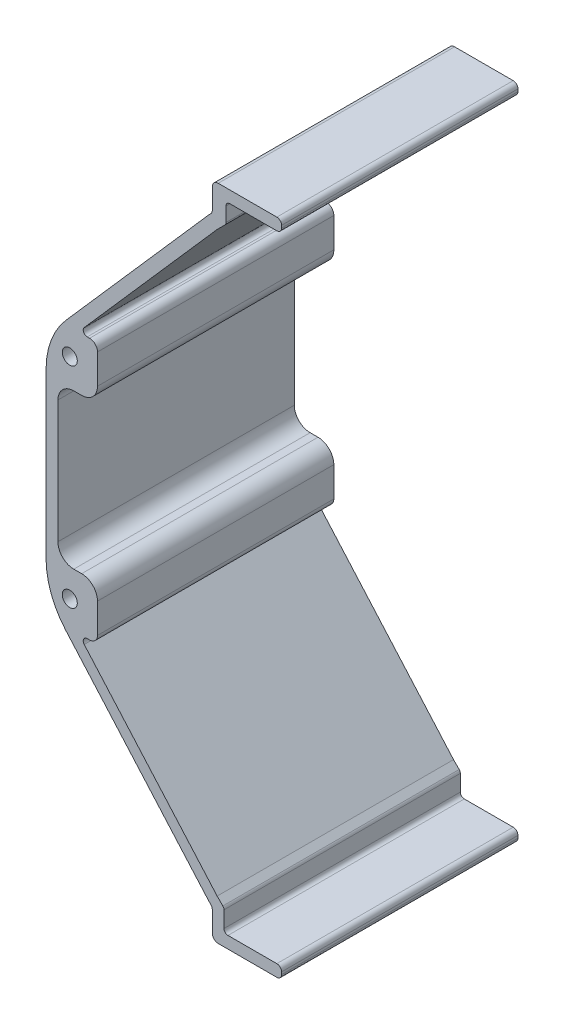
SolidWorks part; units mm, degrees
ref_plane "前视基准面" through (0, 0, 0) normal (0, 0, 1) x (1, 0, 0)
ref_plane "上视基准面" through (0, 0, 0) normal (0, 1, 0) x (1, 0, 0)
ref_plane "右视基准面" through (0, 0, 0) normal (1, 0, 0) x (0, 0, -1)
other "Configuration Table"
sketch "草图1" plane through (0, 0, 0) normal (0, 0, 1) x (1, 0, 0)
  line L0 (-111.7, 80.15) -> (-123.55, 80.15)
  line L1 (-124.55, 79.15) -> (-124.55, 75.5502)
  line L2 (-124.8429, 74.8431) -> (-126.773, 72.913)
  line L3 (-126.773, 72.913) -> (-160.353, 34.6597)
  line L4 (-159.6015, 33) -> (-159, 33)
  line L5 (-157, 31) -> (-157, 23.5)
  line L6 (-161, 19.5) -> (-162.989, 19.5)
  line L7 (-166.989, 15.5) -> (-166.989, -15.5)
  line L8 (-162.989, -19.5) -> (-161, -19.5)
  line L9 (-157, -23.5) -> (-157, -31)
  line L10 (-159, -33) -> (-159.6015, -33)
  line L11 (-160.353, -34.6597) -> (-126.773, -72.913)
  line L12 (-126.773, -72.913) -> (-125.3429, -74.3431)
  line L13 (-125.05, -75.0502) -> (-125.05, -79.15)
  line L14 (-124.05, -80.15) -> (-111.7, -80.15)
  line L15 (-110.5, -81.35) -> (-110.5, -81.95)
  line L16 (-111.7, -83.15) -> (-126.5, -83.15)
  line L17 (-128, -81.65) -> (-128, -76.5503)
  line L18 (-128.4393, -75.4897) -> (-128.963, -74.966)
  line L19 (-128.963, -74.966) -> (-165.023, -33.887)
  line L20 (-169.989, -20.7) -> (-169.989, 20.7)
  line L21 (-165.023, 33.887) -> (-128.963, 74.966)
  line L22 (-128.963, 74.966) -> (-128.4393, 75.4897)
  line L23 (-128, 76.5503) -> (-128, 81.65)
  line L24 (-126.5, 83.15) -> (-111.7, 83.15)
  line L25 (-110.5, 81.95) -> (-110.5, 81.35)
  arc A0 (-123.55, 80.15) -> (-124.55, 79.15) centre (-123.55, 79.15) ccw
  arc A1 (-124.55, 75.5502) -> (-124.8429, 74.8431) centre (-125.55, 75.5502) cw
  arc A2 (-160.353, 34.6597) -> (-159.6015, 33) centre (-159.6015, 34) ccw
  arc A3 (-159, 33) -> (-157, 31) centre (-159, 31) cw
  arc A4 (-157, 23.5) -> (-161, 19.5) centre (-161, 23.5) cw
  arc A5 (-162.989, 19.5) -> (-166.989, 15.5) centre (-162.989, 15.5) ccw
  arc A6 (-166.989, -15.5) -> (-162.989, -19.5) centre (-162.989, -15.5) ccw
  arc A7 (-161, -19.5) -> (-157, -23.5) centre (-161, -23.5) cw
  arc A8 (-157, -31) -> (-159, -33) centre (-159, -31) cw
  arc A9 (-159.6015, -33) -> (-160.353, -34.6597) centre (-159.6015, -34) ccw
  arc A10 (-125.3429, -74.3431) -> (-125.05, -75.0502) centre (-126.05, -75.0502) cw
  arc A11 (-125.05, -79.15) -> (-124.05, -80.15) centre (-124.05, -79.15) ccw
  arc A12 (-111.7, -80.15) -> (-110.5, -81.35) centre (-111.7, -81.35) cw
  arc A13 (-110.5, -81.95) -> (-111.7, -83.15) centre (-111.7, -81.95) cw
  arc A14 (-126.5, -83.15) -> (-128, -81.65) centre (-126.5, -81.65) cw
  arc A15 (-128, -76.5503) -> (-128.4393, -75.4897) centre (-129.5, -76.5503) ccw
  arc A16 (-165.023, -33.887) -> (-169.989, -20.7) centre (-150.0046, -20.7028) cw
  arc A17 (-169.989, 20.7) -> (-165.023, 33.887) centre (-150.0046, 20.7028) cw
  arc A18 (-128.4393, 75.4897) -> (-128, 76.5503) centre (-129.5, 76.5503) ccw
  arc A19 (-128, 81.65) -> (-126.5, 83.15) centre (-126.5, 81.65) cw
  arc A20 (-111.7, 83.15) -> (-110.5, 81.95) centre (-111.7, 81.95) cw
  arc A21 (-110.5, 81.35) -> (-111.7, 80.15) centre (-111.7, 81.35) cw
extrude "凸台-拉伸1" add sketch "草图1" along normal blind 59.7 from offset 29.85
sketch "草图2" plane through (0, 0, 0) normal (0, 0, 1) x (1, 0, 0)
  circle A0 centre (-164, 26.5) radius 1.9
  circle A1 centre (-164, -26.5) radius 1.9
  dimension "D1" = 3.8
  dimension "D2" = 3.8
extrude "切除-拉伸1" cut sketch "草图2" against normal blind 60.7 from offset 30.35
